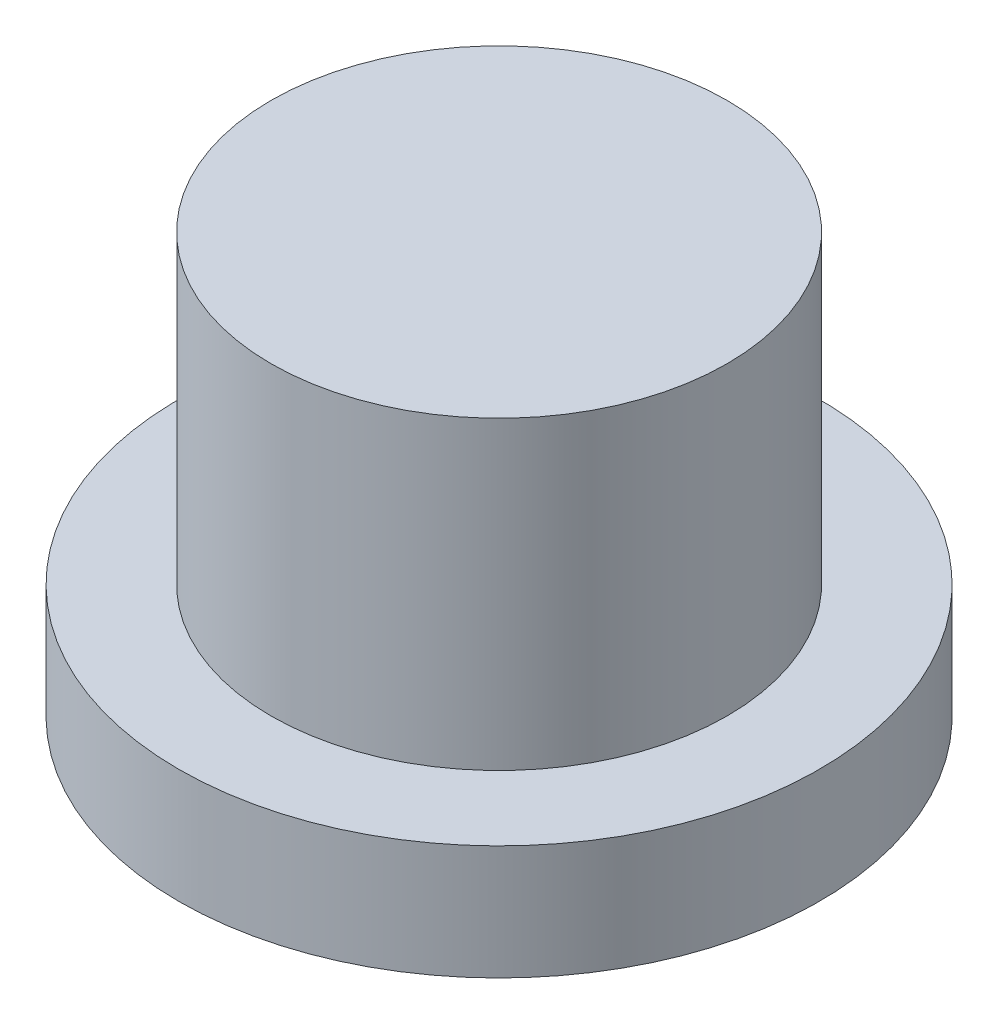
SolidWorks part; units mm, degrees
ref_plane "Alzado" through (0, 0, 0) normal (0, 0, 1) x (1, 0, 0)
ref_plane "Planta" through (0, 0, 0) normal (0, 1, 0) x (1, 0, 0)
ref_plane "Vista lateral" through (0, 0, 0) normal (1, 0, 0) x (0, 0, -1)
sketch "Croquis1" plane through (0, 0, 0) normal (0, 1, 0) x (1, 0, 0)
  circle A0 centre (0, 0) radius 21
  dimension "D1" = 42
extrude "Saliente-Extruir1" add sketch "Croquis1" along normal blind 7.5
sketch "Croquis2" plane through (0, 7.5, 0) normal (0, 1, 0) x (1, 0, 0)
  circle A0 centre (0, 0) radius 14.95
  dimension "D1" = 29.9
extrude "Saliente-Extruir2" add sketch "Croquis2" along normal blind 20
sketch "Croquis3" plane through (0, 0, 0) normal (0, -1, 0) x (1, 0, 0)
  line L0 (-4.995, -4.6152) -> (-7.8942, -4.9562) construction
  line L1 (-4.6152, 4.995) -> (-4.9562, 7.8942) construction
  line L2 (-5.9296, 3.3301) -> (-8.8288, 2.989) construction
  line L3 (-8.8288, 2.989) -> (-18.0646, 0.36) construction
  line L4 (-7.8942, -4.9562) -> (-17.488, -4.5421) construction
  line L5 (-3.3301, -5.9296) -> (-2.989, -8.8288) construction
  line L6 (-2.989, -8.8288) -> (-0.36, -18.0646) construction
  line L7 (4.9562, -7.8942) -> (4.5421, -17.488) construction
  line L8 (4.6152, -4.995) -> (4.9562, -7.8942) construction
  line L9 (5.9296, -3.3301) -> (8.8288, -2.989) construction
  line L10 (8.8288, -2.989) -> (18.0646, -0.36) construction
  line L11 (7.8942, 4.9562) -> (17.488, 4.5421) construction
  line L12 (4.995, 4.6152) -> (7.8942, 4.9562) construction
  line L13 (3.3301, 5.9296) -> (2.989, 8.8288) construction
  line L14 (2.989, 8.8288) -> (0.36, 18.0646) construction
  line L15 (-4.9562, 7.8942) -> (-4.5421, 17.488) construction
  line L16 (-4.995, -4.6152) -> (-7.8942, -4.9562) construction
  line L17 (-4.6152, 4.995) -> (-4.9562, 7.8942) construction
  line L18 (-5.9296, 3.3301) -> (-8.8288, 2.989) construction
  line L19 (-8.8288, 2.989) -> (-18.0646, 0.36) construction
  line L20 (-7.8942, -4.9562) -> (-17.488, -4.5421) construction
  line L21 (-3.3301, -5.9296) -> (-2.989, -8.8288) construction
  line L22 (-2.989, -8.8288) -> (-0.36, -18.0646) construction
  line L23 (4.9562, -7.8942) -> (4.5421, -17.488) construction
  line L24 (4.6152, -4.995) -> (4.9562, -7.8942) construction
  line L25 (5.9296, -3.3301) -> (8.8288, -2.989) construction
  line L26 (8.8288, -2.989) -> (18.0646, -0.36) construction
  line L27 (7.8942, 4.9562) -> (17.488, 4.5421) construction
  line L28 (4.995, 4.6152) -> (7.8942, 4.9562) construction
  line L29 (3.3301, 5.9296) -> (2.989, 8.8288) construction
  line L30 (2.989, 8.8288) -> (0.36, 18.0646) construction
  line L31 (-4.9562, 7.8942) -> (-4.5421, 17.488) construction
  line L32 (-4.9717, -4.8138) -> (-7.8868, -5.1567)
  line L33 (-7.8868, -5.1567) -> (-17.4966, -4.7419)
  line L34 (-8.8681, 3.1858) -> (-18.1194, 0.5524)
  line L35 (-5.953, 3.5287) -> (-8.8681, 3.1858)
  line L36 (-4.8138, 4.9717) -> (-5.1567, 7.8868)
  line L37 (-5.1567, 7.8868) -> (-4.7419, 17.4966)
  line L38 (3.1858, 8.8681) -> (0.5524, 18.1194)
  line L39 (3.5287, 5.953) -> (3.1858, 8.8681)
  line L40 (4.9717, 4.8138) -> (7.8868, 5.1567)
  line L41 (7.8868, 5.1567) -> (17.4966, 4.7419)
  line L42 (8.8681, -3.1858) -> (18.1194, -0.5524)
  line L43 (5.953, -3.5287) -> (8.8681, -3.1858)
  line L44 (4.8138, -4.9717) -> (5.1567, -7.8868)
  line L45 (5.1567, -7.8868) -> (4.7419, -17.4966)
  line L46 (-3.1858, -8.8681) -> (-0.5524, -18.1194)
  line L47 (-3.5287, -5.953) -> (-3.1858, -8.8681)
  arc A0 (-5.9296, 3.3301) -> (-4.6152, 4.995) centre (-6.1049, 4.8198) ccw construction
  arc A1 (-18.0646, 0.36) -> (-17.488, -4.5421) centre (-17.3802, -2.0445) ccw construction
  arc A2 (-3.3301, -5.9296) -> (-4.995, -4.6152) centre (-4.8198, -6.1049) ccw construction
  arc A3 (-0.36, -18.0646) -> (4.5421, -17.488) centre (2.0445, -17.3802) ccw construction
  arc A4 (5.9296, -3.3301) -> (4.6152, -4.995) centre (6.1049, -4.8198) ccw construction
  arc A5 (18.0646, -0.36) -> (17.488, 4.5421) centre (17.3802, 2.0445) ccw construction
  arc A6 (3.3301, 5.9296) -> (4.995, 4.6152) centre (4.8198, 6.1049) ccw construction
  arc A7 (0.36, 18.0646) -> (-4.5421, 17.488) centre (-2.0445, 17.3802) ccw construction
  arc A8 (-5.9296, 3.3301) -> (-4.6152, 4.995) centre (-6.1049, 4.8198) ccw construction
  arc A9 (-18.0646, 0.36) -> (-17.488, -4.5421) centre (-17.3802, -2.0445) ccw construction
  arc A10 (-3.3301, -5.9296) -> (-4.995, -4.6152) centre (-4.8198, -6.1049) ccw construction
  arc A11 (-0.36, -18.0646) -> (4.5421, -17.488) centre (2.0445, -17.3802) ccw construction
  arc A12 (5.9296, -3.3301) -> (4.6152, -4.995) centre (6.1049, -4.8198) ccw construction
  arc A13 (18.0646, -0.36) -> (17.488, 4.5421) centre (17.3802, 2.0445) ccw construction
  arc A14 (3.3301, 5.9296) -> (4.995, 4.6152) centre (4.8198, 6.1049) ccw construction
  arc A15 (0.36, 18.0646) -> (-4.5421, 17.488) centre (-2.0445, 17.3802) ccw construction
  arc A16 (-18.1194, 0.5524) -> (-17.4966, -4.7419) centre (-17.3802, -2.0445) ccw
  arc A17 (-5.953, 3.5287) -> (-4.8138, 4.9717) centre (-6.1049, 4.8198) ccw
  arc A18 (0.5524, 18.1194) -> (-4.7419, 17.4966) centre (-2.0445, 17.3802) ccw
  arc A19 (3.5287, 5.953) -> (4.9717, 4.8138) centre (4.8198, 6.1049) ccw
  arc A20 (18.1194, -0.5524) -> (17.4966, 4.7419) centre (17.3802, 2.0445) ccw
  arc A21 (5.953, -3.5287) -> (4.8138, -4.9717) centre (6.1049, -4.8198) ccw
  arc A22 (-0.5524, -18.1194) -> (4.7419, -17.4966) centre (2.0445, -17.3802) ccw
  arc A23 (-3.5287, -5.953) -> (-4.9717, -4.8138) centre (-4.8198, -6.1049) ccw
  dimension "D1" = 0.2
extrude "Cortar-Extruir1" cut sketch "Croquis3" against normal blind 2.5 and the other way through all
sketch "Croquis4" plane through (0, 2.5, 0) normal (0, -1, 0) x (1, 0, 0)
  circle A0 centre (0, 0) radius 5.5
  dimension "D1" = 11
extrude "Cortar-Extruir2" cut sketch "Croquis4" against normal blind 1.5 and the other way through all
